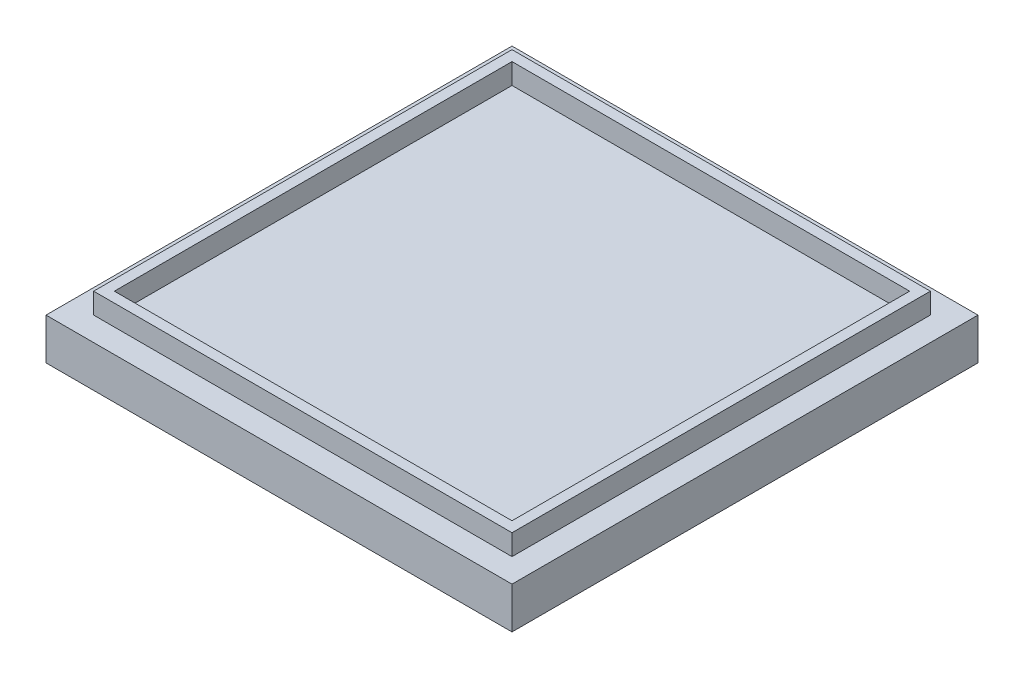
SolidWorks part; units mm, degrees
ref_plane "Front Plane" through (0, 0, 0) normal (0, 0, 1) x (1, 0, 0)
ref_plane "Top Plane" through (0, 0, 0) normal (0, 1, 0) x (1, 0, 0)
ref_plane "Right Plane" through (0, 0, 0) normal (1, 0, 0) x (0, 0, -1)
sketch "Sketch1" plane through (0, 0, 0) normal (0, 1, 0) x (1, 0, 0)
  line L1 (-112.5, -112.5) -> (112.5, -112.5)
  line L2 (-112.5, -112.5) -> (-112.5, 112.5)
  line L3 (-112.5, 112.5) -> (112.5, 112.5)
  line L4 (112.5, -112.5) -> (112.5, 112.5)
  line L5 (-112.5, -112.5) -> (112.5, 112.5) construction
  line L6 (-112.5, 112.5) -> (112.5, -112.5) construction
  point P0 (0, 0)
  dimension "D1" = 225
  dimension "D2" = 225
extrude "Boss-Extrude1" add sketch "Sketch1" along normal blind 20
sketch "Sketch2" plane through (0, 20, 0) normal (0, 1, 0) x (1, 0, 0)
  line L1 (-101, -101) -> (101, -101)
  line L2 (-101, -101) -> (-101, 101)
  line L3 (-101, 101) -> (101, 101)
  line L4 (101, -101) -> (101, 101)
  line L5 (-101, -101) -> (101, 101) construction
  line L6 (-101, 101) -> (101, -101) construction
  line L7 (96, -96) -> (-96, -96)
  line L8 (96, -96) -> (96, 96)
  line L9 (96, 96) -> (-96, 96)
  line L10 (-96, -96) -> (-96, 96)
  line L11 (96, -96) -> (-96, 96) construction
  line L12 (96, 96) -> (-96, -96) construction
  point P0 (0, 0)
  point P6 (0, 0)
  dimension "D1" = 5
  dimension "D2" = 5
  dimension "D3" = 202
extrude "Boss-Extrude2" add sketch "Sketch2" along normal blind 10
equation "\"D2@Sketch1\"=\"D1@Sketch1\""
equation "\"D2@Sketch2\"=\"D1@Sketch2\""
